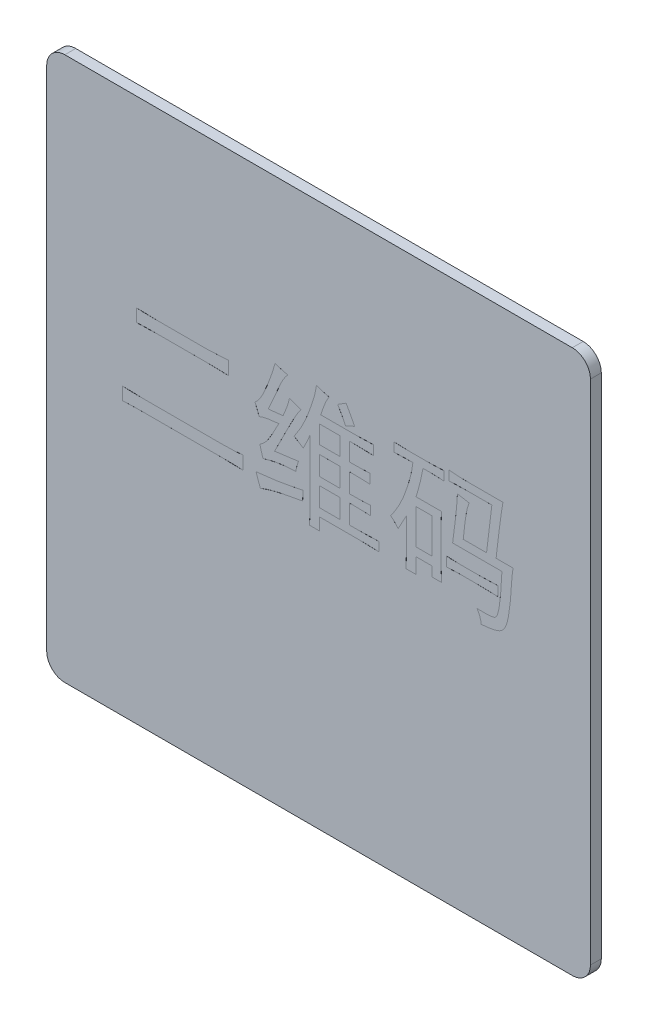
SolidWorks part; units mm, degrees
ref_plane "前视基准面" through (0, 0, 0) normal (0, 0, 1) x (1, 0, 0)
ref_plane "上视基准面" through (0, 0, 0) normal (0, 1, 0) x (1, 0, 0)
ref_plane "右视基准面" through (0, 0, 0) normal (1, 0, 0) x (0, 0, -1)
other "Configuration Table"
sketch "草图1" plane through (0, 0, 0) normal (0, 0, 1) x (1, 0, 0)
  line L1 (-75, -75) -> (75, -75)
  line L2 (-75, -75) -> (-75, 75)
  line L3 (-75, 75) -> (75, 75)
  line L4 (75, -75) -> (75, 75)
  line L5 (-75, -75) -> (75, 75) construction
  line L6 (-75, 75) -> (75, -75) construction
  point P0 (0, 0)
  dimension "D1" = 150
  dimension "D2" = 150
extrude "凸台-拉伸1" add sketch "草图1" along normal blind 3
fillet "圆角1" radius 5 4 edges at (75, -75, 1.5) (-75, -75, 1.5) (-75, 75, 1.5) (75, 75, 1.5)
sketch "草图2" plane through (0, 0, 3) normal (0, 0, 1) x (1, 0, 0)
  line L0 (-75, 0) -> (75, 0) construction
  line L1 (-75, 70) -> (-75, -70) construction
  line L2 (75, -70) -> (75, 70) construction
  text T0 "二维码" font "黑体" height 25
extrude "切除-拉伸1" cut sketch "草图2" against normal blind 0.001
